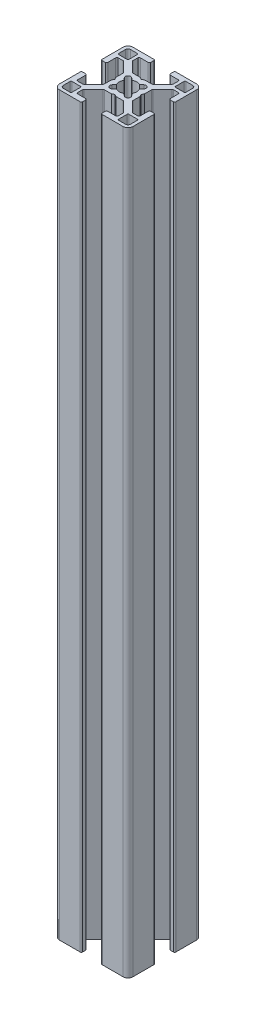
SolidWorks part; units mm, degrees
material "6061 Alloy"
ref_plane "Front Plane" through (0, 0, 0) normal (0, 0, 1) x (1, 0, 0)
ref_plane "Top Plane" through (0, 0, 0) normal (0, 1, 0) x (1, 0, 0)
ref_plane "Right Plane" through (0, 0, 0) normal (1, 0, 0) x (0, 0, -1)
sketch "Sketch1" plane through (0, 0, 0) normal (0, 1, 0) x (1, 0, 0)
  line L0 (296.8106, -41.6994) -> (296.8106, -38.2604)
  line L1 (297.1906, -37.8804) -> (300.6296, -37.8804)
  line L2 (301.0106, -38.2614) -> (301.0106, -41.0804)
  line L3 (300.0106, -42.0804) -> (297.1916, -42.0804)
  line L4 (273.9917, -37.8804) -> (277.4307, -37.8804)
  line L5 (277.8107, -38.2604) -> (277.8107, -41.6994)
  line L6 (277.4297, -42.0804) -> (274.6107, -42.0804)
  line L7 (273.6107, -41.0804) -> (273.6107, -38.2614)
  line L8 (285.8164, -31.5786) -> (284.8373, -32.3604)
  line L9 (283.3307, -30.8538) -> (284.1125, -29.8747)
  line L10 (284.1125, -26.8862) -> (283.3307, -25.9071)
  line L11 (284.8373, -24.4005) -> (285.8164, -25.1823)
  line L12 (288.8049, -25.1823) -> (289.784, -24.4005)
  line L13 (291.2906, -25.9071) -> (290.5088, -26.8862)
  line L14 (290.5088, -29.8747) -> (291.2906, -30.8538)
  line L15 (289.784, -32.3604) -> (288.8049, -31.5786)
  line L16 (277.8107, -15.0615) -> (277.8107, -18.5005)
  line L17 (277.4307, -18.8805) -> (273.9917, -18.8805)
  line L18 (273.6107, -18.4995) -> (273.6107, -15.6805)
  line L19 (274.6107, -14.6805) -> (277.4297, -14.6805)
  line L20 (297.1916, -14.6805) -> (300.0106, -14.6805)
  line L21 (301.0106, -15.6805) -> (301.0106, -18.4995)
  line L22 (300.6296, -18.8805) -> (297.1906, -18.8805)
  line L23 (296.8106, -18.5005) -> (296.8106, -15.0615)
  line L24 (300.0531, -32.8804) -> (300.0531, -36.113)
  line L25 (299.5534, -36.6304) -> (297.5708, -36.6304)
  line L26 (297.2173, -36.484) -> (293.2917, -32.5584)
  line L27 (293.1453, -32.2049) -> (293.1453, -29.3929)
  line L28 (293.1453, -29.3929) -> (292.6353, -28.4429)
  line L29 (292.6353, -28.4429) -> (293.1453, -27.4929)
  line L30 (293.1453, -27.4929) -> (293.1453, -24.556)
  line L31 (293.2917, -24.2024) -> (297.2173, -20.2769)
  line L32 (297.5708, -20.1305) -> (299.5534, -20.1305)
  line L33 (300.0531, -20.6479) -> (300.0531, -23.8804)
  line L34 (300.5531, -24.3804) -> (301.8106, -24.3804)
  line L35 (302.3106, -23.8804) -> (302.3106, -15.3805)
  line L36 (300.3106, -13.3805) -> (291.8106, -13.3805)
  line L37 (291.3106, -13.8805) -> (291.3106, -15.138)
  line L38 (291.8106, -15.638) -> (295.0431, -15.638)
  line L39 (295.5606, -16.1377) -> (295.5606, -18.1203)
  line L40 (295.4142, -18.4738) -> (291.4886, -22.3993)
  line L41 (291.1351, -22.5458) -> (288.2606, -22.5458)
  line L42 (288.2606, -22.5458) -> (287.3106, -23.0558)
  line L43 (287.3106, -23.0558) -> (286.3606, -22.5458)
  line L44 (286.3606, -22.5458) -> (283.4862, -22.5458)
  line L45 (283.1326, -22.3993) -> (279.2071, -18.4738)
  line L46 (279.0607, -18.1203) -> (279.0607, -16.1377)
  line L47 (279.5781, -15.638) -> (282.8106, -15.638)
  line L48 (283.3106, -15.138) -> (283.3106, -13.8805)
  line L49 (282.8106, -13.3805) -> (274.3107, -13.3805)
  line L50 (272.3107, -15.3805) -> (272.3107, -23.8804)
  line L51 (272.8107, -24.3804) -> (274.0682, -24.3804)
  line L52 (274.5682, -23.8804) -> (274.5682, -20.6479)
  line L53 (275.0678, -20.1305) -> (277.0504, -20.1305)
  line L54 (277.404, -20.2769) -> (281.3295, -24.2024)
  line L55 (281.476, -24.556) -> (281.476, -27.4929)
  line L56 (281.476, -27.4929) -> (281.986, -28.4429)
  line L57 (281.986, -28.4429) -> (281.476, -29.3929)
  line L58 (281.476, -29.3929) -> (281.476, -32.2049)
  line L59 (281.3295, -32.5584) -> (277.404, -36.484)
  line L60 (277.0504, -36.6304) -> (275.0678, -36.6304)
  line L61 (274.5682, -36.113) -> (274.5682, -32.8804)
  line L62 (274.0682, -32.3804) -> (272.8107, -32.3804)
  line L63 (272.3107, -32.8804) -> (272.3107, -41.3804)
  line L64 (274.3107, -43.3804) -> (282.8106, -43.3804)
  line L65 (283.3106, -42.8804) -> (283.3106, -41.6229)
  line L66 (282.8106, -41.1229) -> (279.5781, -41.1229)
  line L67 (279.0607, -40.6232) -> (279.0607, -38.6406)
  line L68 (279.2071, -38.2871) -> (283.1326, -34.3616)
  line L69 (283.4862, -34.2151) -> (286.3606, -34.2151)
  line L70 (286.3606, -34.2151) -> (287.3106, -33.7051)
  line L71 (287.3106, -33.7051) -> (288.2606, -34.2151)
  line L72 (288.2606, -34.2151) -> (291.1351, -34.2151)
  line L73 (291.4886, -34.3616) -> (295.4142, -38.2871)
  line L74 (295.5606, -38.6406) -> (295.5606, -40.6232)
  line L75 (295.0431, -41.1229) -> (291.8106, -41.1229)
  line L76 (291.3106, -41.6229) -> (291.3106, -42.8804)
  line L77 (291.8106, -43.3804) -> (300.3106, -43.3804)
  line L78 (302.3106, -41.3804) -> (302.3106, -32.8804)
  line L79 (301.8106, -32.3804) -> (300.5531, -32.3804)
  arc A0 (296.8106, -41.6994) -> (297.1916, -42.0804) centre (297.1916, -41.6994) ccw
  arc A1 (297.1906, -37.8804) -> (296.8106, -38.2604) centre (297.1906, -38.2604) ccw
  arc A2 (301.0106, -38.2614) -> (300.6296, -37.8804) centre (300.6296, -38.2614) ccw
  arc A3 (300.0106, -42.0804) -> (301.0106, -41.0804) centre (300.0106, -41.0804) ccw
  arc A4 (273.9917, -37.8804) -> (273.6107, -38.2614) centre (273.9917, -38.2614) ccw
  arc A5 (277.8107, -38.2604) -> (277.4307, -37.8804) centre (277.4307, -38.2604) ccw
  arc A6 (277.4297, -42.0804) -> (277.8107, -41.6994) centre (277.4297, -41.6994) ccw
  arc A7 (273.6107, -41.0804) -> (274.6107, -42.0804) centre (274.6107, -41.0804) ccw
  arc A8 (285.8164, -31.5786) -> (288.8049, -31.5786) centre (287.3106, -28.3804) ccw
  arc A9 (283.3307, -30.8538) -> (284.8373, -32.3604) centre (284.1684, -31.5227) ccw
  arc A10 (284.1125, -26.8862) -> (284.1125, -29.8747) centre (287.3106, -28.3804) ccw
  arc A11 (284.8373, -24.4005) -> (283.3307, -25.9071) centre (284.1684, -25.2382) ccw
  arc A12 (288.8049, -25.1823) -> (285.8164, -25.1823) centre (287.3106, -28.3804) ccw
  arc A13 (291.2906, -25.9071) -> (289.784, -24.4005) centre (290.4528, -25.2382) ccw
  arc A14 (290.5088, -29.8747) -> (290.5088, -26.8862) centre (287.3106, -28.3804) ccw
  arc A15 (289.784, -32.3604) -> (291.2906, -30.8538) centre (290.4528, -31.5227) ccw
  arc A16 (277.8107, -15.0615) -> (277.4297, -14.6805) centre (277.4297, -15.0615) ccw
  arc A17 (277.4307, -18.8805) -> (277.8107, -18.5005) centre (277.4307, -18.5005) ccw
  arc A18 (273.6107, -18.4995) -> (273.9917, -18.8805) centre (273.9917, -18.4995) ccw
  arc A19 (274.6107, -14.6805) -> (273.6107, -15.6805) centre (274.6107, -15.6805) ccw
  arc A20 (297.1916, -14.6805) -> (296.8106, -15.0615) centre (297.1916, -15.0615) ccw
  arc A21 (301.0106, -15.6805) -> (300.0106, -14.6805) centre (300.0106, -15.6805) ccw
  arc A22 (300.6296, -18.8805) -> (301.0106, -18.4995) centre (300.6296, -18.4995) ccw
  arc A23 (296.8106, -18.5005) -> (297.1906, -18.8805) centre (297.1906, -18.5005) ccw
  arc A24 (300.5531, -32.3804) -> (300.0531, -32.8804) centre (300.5531, -32.8804) ccw
  arc A25 (299.5534, -36.6304) -> (300.0531, -36.113) centre (299.5534, -36.1304) ccw
  arc A26 (297.2173, -36.484) -> (297.5708, -36.6304) centre (297.5708, -36.1304) ccw
  arc A27 (293.1453, -32.2049) -> (293.2917, -32.5584) centre (293.6453, -32.2049) ccw
  arc A28 (293.2917, -24.2024) -> (293.1453, -24.556) centre (293.6453, -24.556) ccw
  arc A29 (297.5708, -20.1305) -> (297.2173, -20.2769) centre (297.5708, -20.6305) ccw
  arc A30 (300.0531, -20.6479) -> (299.5534, -20.1305) centre (299.5534, -20.6305) ccw
  arc A31 (300.0531, -23.8804) -> (300.5531, -24.3804) centre (300.5531, -23.8804) ccw
  arc A32 (301.8106, -24.3804) -> (302.3106, -23.8804) centre (301.8106, -23.8804) ccw
  arc A33 (302.3106, -15.3805) -> (300.3106, -13.3805) centre (300.3106, -15.3805) ccw
  arc A34 (291.8106, -13.3805) -> (291.3106, -13.8805) centre (291.8106, -13.8805) ccw
  arc A35 (291.3106, -15.138) -> (291.8106, -15.638) centre (291.8106, -15.138) ccw
  arc A36 (295.5606, -16.1377) -> (295.0431, -15.638) centre (295.0606, -16.1377) ccw
  arc A37 (295.4142, -18.4738) -> (295.5606, -18.1203) centre (295.0606, -18.1203) ccw
  arc A38 (291.1351, -22.5458) -> (291.4886, -22.3993) centre (291.1351, -22.0458) ccw
  arc A39 (283.1326, -22.3993) -> (283.4862, -22.5458) centre (283.4862, -22.0458) ccw
  arc A40 (279.0607, -18.1203) -> (279.2071, -18.4738) centre (279.5607, -18.1203) ccw
  arc A41 (279.5781, -15.638) -> (279.0607, -16.1377) centre (279.5607, -16.1377) ccw
  arc A42 (282.8106, -15.638) -> (283.3106, -15.138) centre (282.8106, -15.138) ccw
  arc A43 (283.3106, -13.8805) -> (282.8106, -13.3805) centre (282.8106, -13.8805) ccw
  arc A44 (274.3107, -13.3805) -> (272.3107, -15.3805) centre (274.3107, -15.3805) ccw
  arc A45 (272.3107, -23.8804) -> (272.8107, -24.3804) centre (272.8107, -23.8804) ccw
  arc A46 (274.0682, -24.3804) -> (274.5682, -23.8804) centre (274.0682, -23.8804) ccw
  arc A47 (275.0678, -20.1305) -> (274.5682, -20.6479) centre (275.0678, -20.6305) ccw
  arc A48 (277.404, -20.2769) -> (277.0504, -20.1305) centre (277.0504, -20.6305) ccw
  arc A49 (281.476, -24.556) -> (281.3295, -24.2024) centre (280.976, -24.556) ccw
  arc A50 (281.3295, -32.5584) -> (281.476, -32.2049) centre (280.976, -32.2049) ccw
  arc A51 (277.0504, -36.6304) -> (277.404, -36.484) centre (277.0504, -36.1304) ccw
  arc A52 (274.5682, -36.113) -> (275.0678, -36.6304) centre (275.0678, -36.1304) ccw
  arc A53 (274.5682, -32.8804) -> (274.0682, -32.3804) centre (274.0682, -32.8804) ccw
  arc A54 (272.8107, -32.3804) -> (272.3107, -32.8804) centre (272.8107, -32.8804) ccw
  arc A55 (272.3107, -41.3804) -> (274.3107, -43.3804) centre (274.3107, -41.3804) ccw
  arc A56 (282.8106, -43.3804) -> (283.3106, -42.8804) centre (282.8106, -42.8804) ccw
  arc A57 (283.3106, -41.6229) -> (282.8106, -41.1229) centre (282.8106, -41.6229) ccw
  arc A58 (279.0607, -40.6232) -> (279.5781, -41.1229) centre (279.5607, -40.6232) ccw
  arc A59 (279.2071, -38.2871) -> (279.0607, -38.6406) centre (279.5607, -38.6406) ccw
  arc A60 (283.4862, -34.2151) -> (283.1326, -34.3616) centre (283.4862, -34.7151) ccw
  arc A61 (291.4886, -34.3616) -> (291.1351, -34.2151) centre (291.1351, -34.7151) ccw
  arc A62 (295.5606, -38.6406) -> (295.4142, -38.2871) centre (295.0606, -38.6406) ccw
  arc A63 (295.0431, -41.1229) -> (295.5606, -40.6232) centre (295.0606, -40.6232) ccw
  arc A64 (291.8106, -41.1229) -> (291.3106, -41.6229) centre (291.8106, -41.6229) ccw
  arc A65 (291.3106, -42.8804) -> (291.8106, -43.3804) centre (291.8106, -42.8804) ccw
  arc A66 (300.3106, -43.3804) -> (302.3106, -41.3804) centre (300.3106, -41.3804) ccw
  arc A67 (302.3106, -32.8804) -> (301.8106, -32.3804) centre (301.8106, -32.8804) ccw
extrude "Extrude1" add sketch "Sketch1" along normal blind 300
